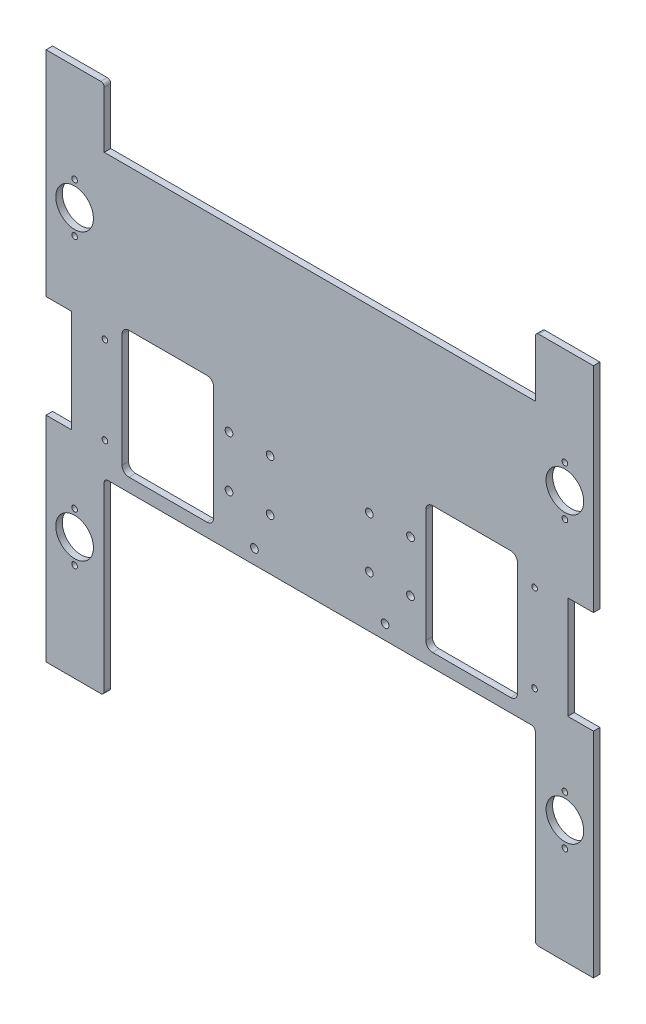
SolidWorks part; units mm, degrees
ref_plane "Front Plane" through (0, 0, 0) normal (0, 0, 1) x (1, 0, 0)
ref_plane "Top Plane" through (0, 0, 0) normal (0, 1, 0) x (1, 0, 0)
ref_plane "Right Plane" through (0, 0, 0) normal (1, 0, 0) x (0, 0, -1)
ref_plane "Plane1" through (0, 150, 0) normal (0, 1, 0) x (1, 0, 0)
ref_plane "Plane2" through (0, -150, 0) normal (0, 1, 0) x (1, 0, 0)
ref_plane "Plane3" through (150, 0, 0) normal (1, 0, 0) x (0, 0, -1)
ref_plane "Plane4" through (-150, 0, 0) normal (1, 0, 0) x (0, 0, -1)
sketch "Sketch2" plane through (0, 0, 0) normal (0, 0, 1) x (1, 0, 0)
  line L0 (0, -10.2) -> (0, 50.0764) construction
  line L5 (-53.06, 39.945) -> (-53.06, 10.055) construction
  line L23 (-160, 180) -> (-128, 180)
  line L24 (139.6652, 116) -> (168.3348, 116) construction
  line L31 (-160, -130) -> (-128, -130)
  line L40 (-152.1866, -81.0661) -> (-123.5266, -81.0661) construction
  line L42 (-126, 178) -> (-126, 145.0725)
  line L43 (-126, 145.0725) -> (126, 145.0725)
  line L47 (-66, 62.1714) -> (-111.5977, 62.1714)
  line L48 (66, 62.1714) -> (111.5977, 62.1714)
  line L49 (62, 58.1714) -> (62, -8.1714)
  line L50 (66, -12.1714) -> (111.5977, -12.1714)
  line L51 (115.5977, 58.1714) -> (115.5977, -8.1714)
  line L52 (62, 62.1714) -> (115.5977, -12.1714) construction
  line L53 (62, -12.1714) -> (115.5977, 62.1714) construction
  line L54 (-62, 58.1714) -> (-62, -8.1714)
  line L55 (-66, -12.1714) -> (-111.5977, -12.1714)
  line L56 (-115.5977, 58.1714) -> (-115.5977, -8.1714)
  line L57 (177.1787, -66.0847) -> (177.1787, 11.9153) construction
  line L70 (-125.5977, 50.5) -> (-125.5977, -0.5) construction
  line L73 (-160, 180) -> (-160, 55)
  line L74 (162.5, 25) -> (139.6652, 25) construction
  line L75 (-126, -128) -> (-126, -22)
  line L76 (-124, -20) -> (124, -20)
  line L79 (-160, -5) -> (-160, -130)
  line L80 (-160, -5) -> (-145, -5)
  line L82 (-160, 55) -> (-145, 55)
  line L83 (-145, -5) -> (-145, 55)
  line L84 (-145.4163, 25) -> (-145, 55) construction
  line L85 (-145.4163, 25) -> (-145, -5) construction
  line L88 (145.4163, 25) -> (145, -5) construction
  line L89 (145.4163, 25) -> (145, 55) construction
  line L90 (125.5977, 50.5) -> (125.5977, -0.5) construction
  line L91 (145, -5) -> (145, 55)
  line L92 (160, 55) -> (145, 55)
  line L93 (160, -5) -> (145, -5)
  line L94 (160, -5) -> (160, -130)
  line L95 (160, 180) -> (160, 55)
  line L96 (126, -128) -> (126, -22)
  line L97 (160, -130) -> (128, -130)
  line L98 (160, 180) -> (128, 180)
  line L99 (126, 178) -> (126, 145.0725)
  circle A1 centre (-143.3292, 122.686) radius 1.65
  circle A2 centre (-143.3292, 94.0163) radius 1.65
  circle A3 centre (143.3292, 122.686) radius 1.65
  circle A4 centre (143.3292, 94.0163) radius 1.65
  circle A9 centre (143.3292, 108.3512) radius 11
  circle A10 centre (-143.3292, 108.3512) radius 11
  circle A17 centre (125.5977, -0.5) radius 1.65
  circle A18 centre (125.5977, 50.5) radius 1.65
  circle A19 centre (-125.5977, -0.5) radius 1.65
  circle A20 centre (-125.5977, 50.5) radius 1.65
  circle A27 centre (-29, 10.055) radius 2.25
  circle A32 centre (-29, 39.945) radius 2.25
  circle A33 centre (-53.06, 39.945) radius 2.25
  circle A34 centre (-53.06, 10.055) radius 2.25
  circle A35 centre (53.06, 10.055) radius 2.25
  circle A36 centre (29, 10.055) radius 2.25
  circle A37 centre (29, 39.945) radius 2.25
  circle A38 centre (53.06, 39.945) radius 2.25
  arc A47 (-126, 178) -> (-128, 180) centre (-128, 178) ccw
  arc A48 (62, -8.1714) -> (66, -12.1714) centre (66, -8.1714) ccw
  arc A49 (111.5977, -12.1714) -> (115.5977, -8.1714) centre (111.5977, -8.1714) ccw
  arc A50 (111.5977, 62.1714) -> (115.5977, 58.1714) centre (111.5977, 58.1714) cw
  arc A51 (66, 62.1714) -> (62, 58.1714) centre (66, 58.1714) ccw
  arc A52 (-111.5977, 62.1714) -> (-115.5977, 58.1714) centre (-111.5977, 58.1714) ccw
  arc A53 (-66, 62.1714) -> (-62, 58.1714) centre (-66, 58.1714) cw
  arc A54 (-62, -8.1714) -> (-66, -12.1714) centre (-66, -8.1714) cw
  arc A55 (-111.5977, -12.1714) -> (-115.5977, -8.1714) centre (-111.5977, -8.1714) cw
  circle A68 centre (143.3292, -72.686) radius 1.65
  circle A69 centre (143.3292, -44.0163) radius 1.65
  circle A70 centre (143.3292, -58.3512) radius 11
  circle A71 centre (-143.3292, -58.3512) radius 11
  circle A72 centre (-143.3292, -44.0163) radius 1.65
  circle A73 centre (-143.3292, -72.686) radius 1.65
  arc A76 (-126, -22) -> (-124, -20) centre (-124, -22) cw
  arc A77 (-126, -128) -> (-128, -130) centre (-128, -128) cw
  arc A79 (126, -22) -> (124, -20) centre (124, -22) ccw
  arc A80 (126, -128) -> (128, -130) centre (128, -128) ccw
  arc A81 (126, 178) -> (128, 180) centre (128, 178) cw
  circle A82 centre (38.1799, -11.5638) radius 2.25
  circle A83 centre (-38.1799, -11.5638) radius 2.25
  point P0 (0, 0)
  point P2 (0, 0)
  point P4 (0, 150)
  point P7 (-145.4163, 25)
  point P11 (-125.5977, 25)
  point P12 (88.7989, 25)
  point P23 (-53.06, 25)
  point P24 (0, -20)
  point P33 (-145, 25)
  point P82 (177.1787, -27.0847)
  point P108 (0, 0)
  point P111 (-115.5977, 25)
  point P112 (145.4163, 25)
  point P122 (0, 145.0725)
  point P130 (-134.3292, -58.3512)
  point P132 (-62, 25)
  point P141 (-142.9479, -59.1692)
  point P142 (-143.3292, -58.3512)
  dimension "D3" = 51
  dimension "D7" = 160
  dimension "D8" = 3.3
  dimension "D9" = 126
  dimension "D10" = 22
  dimension "D11" = 74.3428
  dimension "D13" = 53.5977
  dimension "D16" = 62
  dimension "D17" = 15
  dimension "D18" = 60
  dimension "D19" = 3.3
  dimension "D6" = 14.3348
  dimension "D20" = 14.3348
  dimension "D21" = 155
  dimension "D23" = 4.5
  dimension "D24" = 45
  dimension "D25" = 4.5
  dimension "D26" = 4.5
  dimension "D27" = 29.89
  dimension "D29" = 24.06
  dimension "D31" = 4
  dimension "D32" = 155
  dimension "D4" = 3.3
  dimension "D5" = 10
  dimension "D22" = 29.89
  dimension "D28" = 24.06
  dimension "D30" = 29
  dimension "D14" = 2
extrude "Boss-Extrude1" add sketch "Sketch2" along normal blind 3.8
